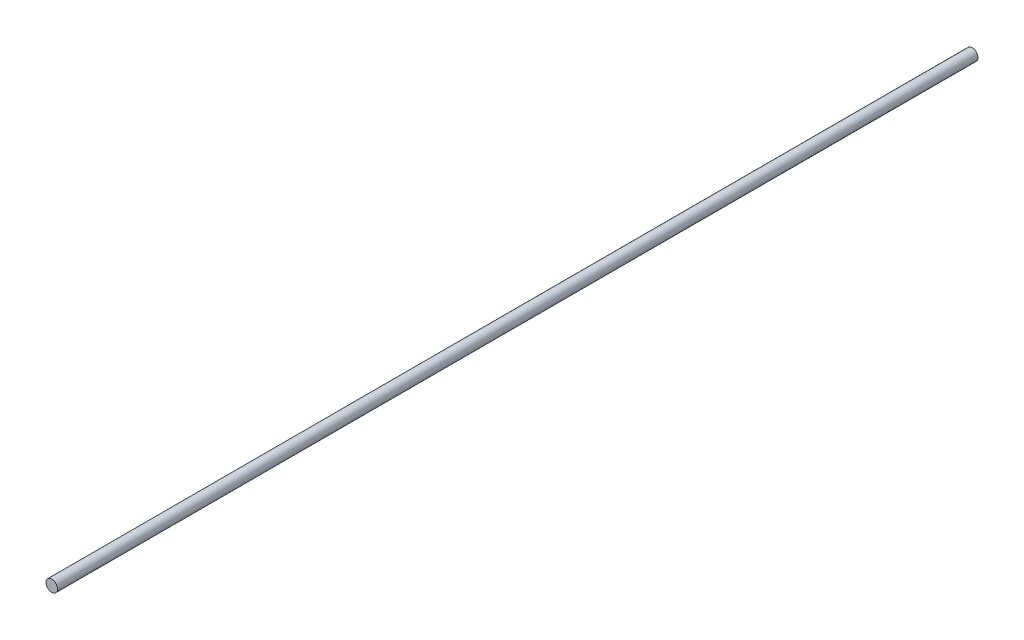
SolidWorks part; units mm, degrees
ref_plane "Front" through (0, 0, 0) normal (0, 0, 1) x (1, 0, 0)
ref_plane "Top" through (0, 0, 0) normal (0, 1, 0) x (1, 0, 0)
ref_plane "Right" through (0, 0, 0) normal (1, 0, 0) x (0, 0, -1)
sketch "Sketch1" plane through (0, 0, 0) normal (0, 0, 1) x (1, 0, 0)
  circle A0 centre (0, 0) radius 2.5
extrude "Boss-Extrude1" add sketch "Sketch1" along normal blind 400
